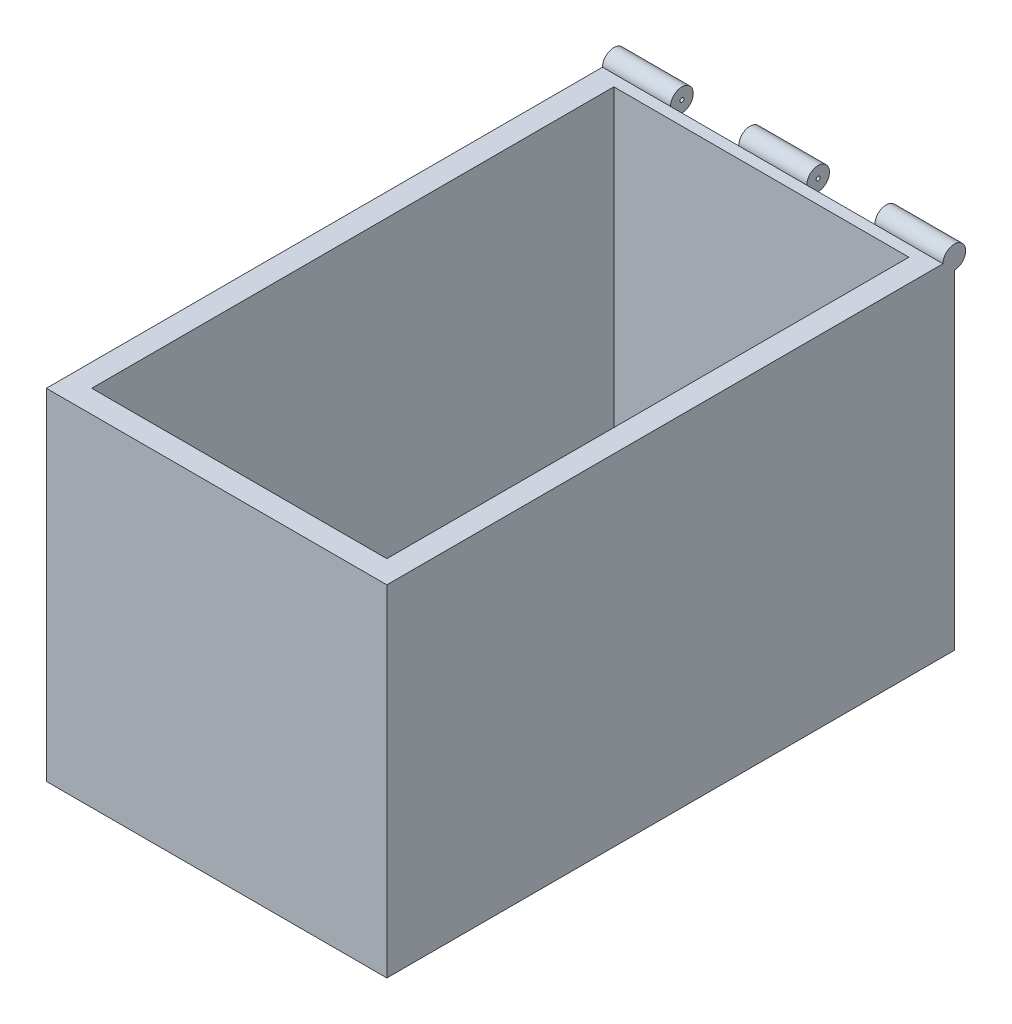
SolidWorks part; units mm, degrees
ref_plane "Front Plane" through (0, 0, 0) normal (0, 0, 1) x (1, 0, 0)
ref_plane "Top Plane" through (0, 0, 0) normal (0, 1, 0) x (1, 0, 0)
ref_plane "Right Plane" through (0, 0, 0) normal (1, 0, 0) x (0, 0, -1)
sketch "Sketch1" plane through (0, 0, 0) normal (0, 0, 1) x (1, 0, 0)
  line L0 (0, 0) -> (0, 150) construction
  line L2 (0, 0) -> (150, 0)
  line L3 (0, 0) -> (0, 150)
  line L4 (0, 150) -> (150, 150)
  line L5 (150, 0) -> (150, 150)
  dimension "D1" = 150
  dimension "D2" = 150
extrude "Boss-Extrude1" add sketch "Sketch1" along normal blind 250
shell "Shell1" thickness 10
sketch "Sketch3" plane through (0, 0, 0) normal (0, 1, 0) x (1, 0, 0)
  line L0 (75, 0) -> (75, -250) construction
  line L1 (150, 0) -> (0, 0) construction
  line L2 (150, -250) -> (0, -250) construction
  line L3 (75, -125) -> (0, -125) construction
  line L4 (0, -250) -> (0, 0) construction
  line L5 (75, -125) -> (150, -125) construction
  line L6 (150, -250) -> (150, 0) construction
  line L7 (10, -10) -> (140, -10) construction
  line L8 (15, -235) -> (135, -235)
  line L9 (15, -235) -> (15, -15)
  line L10 (15, -15) -> (135, -15)
  line L11 (135, -235) -> (135, -15)
  line L12 (10, -240) -> (140, -240) construction
  line L14 (140, -240) -> (140, -10) construction
  line L15 (10, -240) -> (10, -10) construction
  line L17 (20, -230) -> (130, -230)
  line L18 (20, -230) -> (20, -20)
  line L19 (20, -20) -> (130, -20)
  line L20 (130, -230) -> (130, -20)
  dimension "D1" = 5
  dimension "D2" = 5
  dimension "D3" = 5
  dimension "D4" = 5
  dimension "D5" = 5
  dimension "D6" = 5
  dimension "D7" = 5
  dimension "D8" = 5
  dimension "D9" = 210
  dimension "D10" = 110
extrude "Boss-Extrude2" add sketch "Sketch3" along normal blind 0.001
sketch "Sketch4" plane through (0, 0, 0) normal (0, 1, 0) x (1, 0, 0)
  line L7 (40, -230) -> (110, -230)
  line L12 (40, -20) -> (110, -20)
  line L19 (10, -10) -> (140, -10) construction
  line L20 (40, -10) -> (110, -10)
  line L21 (40, -20) -> (40, -10)
  line L22 (110, -20) -> (110, -10)
  line L24 (10, -240) -> (140, -240) construction
  line L25 (110, -240) -> (40, -240)
  line L26 (140, -240) -> (10, -240) construction
  line L28 (110, -240) -> (110, -230)
  line L29 (40, -230) -> (40, -240)
  dimension "D3" = 10
  dimension "D6" = 10
extrude "Boss-Extrude3" add sketch "Sketch4" along normal blind 40
ref_plane "Plane1" through (0, 150, 0) normal (0, 1, 0) x (1, 0, 0)
sketch "Sketch5" plane through (0, 0, 0) normal (-1, 0, 0) x (0, 0, 1)
  line L0 (250, 150) -> (0, 150) construction
  line L1 (0, 150) -> (0, 0) construction
  circle A0 centre (0, 150) radius 5
  point P4 (0, 150)
  dimension "D1" = 10
extrude "Boss-Extrude4" add sketch "Sketch5" against normal blind 30 contours A0
sketch "Sketch6" plane through (30, 0, 0) normal (1, 0, 0) x (0, 0, -1)
  circle A0 centre (0, 150) radius 5
extrude "Cut-Extrude2" cut sketch "Sketch6" along normal blind 30
sketch "Sketch7" plane through (60, 0, 0) normal (-1, 0, 0) x (0, 0, 1)
  circle A0 centre (0, 150) radius 5
  dimension "D1" = 10
extrude "Boss-Extrude5" add sketch "Sketch7" against normal blind 30
sketch "Sketch8" plane through (90, 0, 0) normal (1, 0, 0) x (0, 0, -1)
  circle A0 centre (0, 150) radius 5
  dimension "D1" = 10
extrude "Cut-Extrude3" cut sketch "Sketch8" along normal blind 30
sketch "Sketch9" plane through (120, 0, 0) normal (-1, 0, 0) x (0, 0, 1)
  circle A0 centre (0, 150) radius 5
  dimension "D1" = 10
extrude "Boss-Extrude6" add sketch "Sketch9" against normal blind 30
sketch "Sketch10" plane through (0, 0, 0) normal (-1, 0, 0) x (0, 0, 1)
  circle A0 centre (0, 150) radius 0.875
  dimension "D1" = 1.75
extrude "Cut-Extrude4" cut sketch "Sketch10" against normal blind 145
